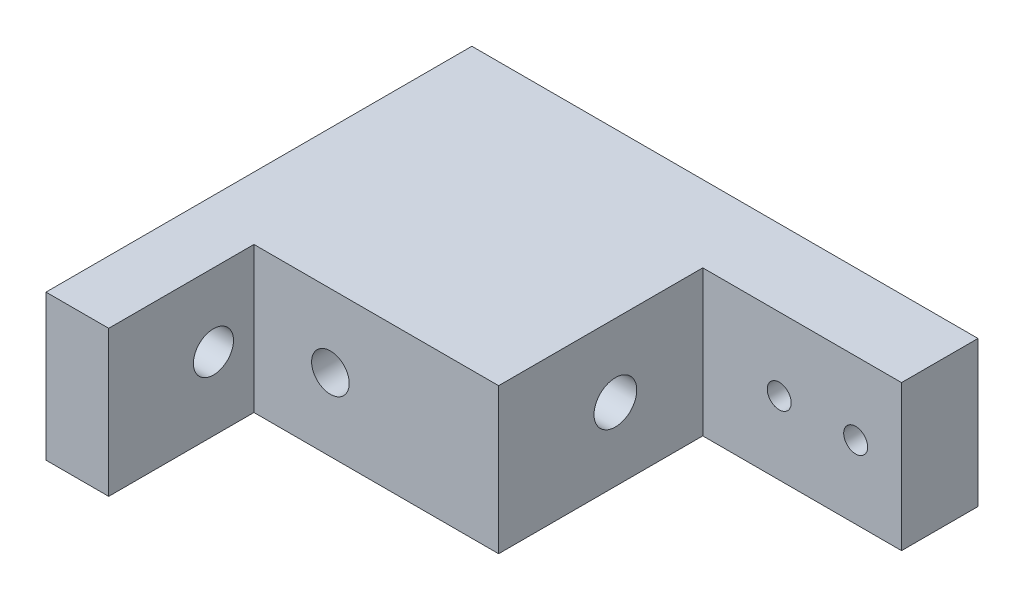
SolidWorks part; units mm, degrees
ref_plane "Front Plane" through (0, 0, 0) normal (0, 0, 1) x (1, 0, 0)
ref_plane "Top Plane" through (0, 0, 0) normal (0, 1, 0) x (1, 0, 0)
ref_plane "Right Plane" through (0, 0, 0) normal (1, 0, 0) x (0, 0, -1)
ref_plane "Plane1" through (0, -4.76, 0) normal (0, -1, 0) x (1, 0, 0)
sketch "Sketch1" plane through (0, -4.76, 0) normal (0, -1, 0) x (1, 0, 0)
  line L0 (-23.6, 0) -> (9.5, 0)
  line L1 (9.5, 0) -> (9.5, 27.85)
  line L2 (9.5, 27.85) -> (-23.6, 27.85)
  line L3 (-23.6, 27.85) -> (-23.6, 0)
extrude "Boss-Extrude1" add sketch "Sketch1" against normal blind 9.52
sketch "Sketch2" plane through (0, 4.76, 0) normal (0, 1, 0) x (-1, 0, 0)
  line L0 (-9.5, 5) -> (3.5, 5)
  line L1 (3.5, 5) -> (3.5, 27.85)
  line L2 (3.5, 27.85) -> (-9.5, 27.85)
  line L3 (-9.5, 27.85) -> (-9.5, 5)
extrude "Cut-Extrude1" cut sketch "Sketch2" against normal through all
sketch "Sketch3" plane through (0, 4.76, 0) normal (0, 1, 0) x (-1, 0, 0)
  line L0 (3.5, 18.35) -> (19.5, 18.35)
  line L1 (19.5, 18.35) -> (19.5, 27.85)
  line L2 (19.5, 27.85) -> (3.5, 27.85)
  line L3 (3.5, 27.85) -> (3.5, 18.35)
extrude "Cut-Extrude2" cut sketch "Sketch3" against normal through all
sketch "Sketch4" plane through (0, 0, 0) normal (0, 1, 0) x (1, 0, 0)
  line L0 (7.2835, 0) -> (6.5, 0)
  line L1 (6.5, 0) -> (6.5, -5)
  line L2 (6.5, -5) -> (7.2835, -5)
  line L3 (7.2835, -5) -> (7.2835, -2)
  line L4 (7.2835, -2) -> (7.2835, 0)
  line L5 (6.5, 0) -> (6.5, -5) construction
revolve "Cut-Revolve1" cut sketch "Sketch4" angle 360 about L5
sketch "Sketch5" plane through (0, 0, 0) normal (0, 1, 0) x (1, 0, 0)
  line L0 (2.2835, 0) -> (1.5, 0)
  line L1 (1.5, 0) -> (1.5, -5)
  line L2 (1.5, -5) -> (2.2835, -5)
  line L3 (2.2835, -5) -> (2.2835, -2)
  line L4 (2.2835, -2) -> (2.2835, 0)
  line L5 (1.5, 0) -> (1.5, -5) construction
revolve "Cut-Revolve2" cut sketch "Sketch5" angle 360 about L5
ref_plane "Plane2" through (0, 0, 0) normal (0, -1, 0) x (1, 0, 0)
sketch "Sketch6" plane through (0, 0, 0) normal (0, -1, 0) x (1, 0, 0)
  line L0 (-13.2705, 18.35) -> (-14.5, 18.35)
  line L1 (-14.5, 18.35) -> (-14.5, 8.35)
  line L2 (-14.5, 8.35) -> (-13.2705, 8.35)
  line L3 (-13.2705, 8.35) -> (-13.2705, 16.35)
  line L4 (-13.2705, 16.35) -> (-13.2705, 18.35)
  line L5 (-14.5, 18.35) -> (-14.5, 8.35) construction
revolve "Cut-Revolve3" cut sketch "Sketch6" angle 360 about L5
ref_plane "Plane3" through (0, 0, 21) normal (0, 0, 1) x (1, 0, 0)
sketch "Sketch7" plane through (0, 0, 21) normal (0, 0, 1) x (1, 0, 0)
  line L0 (-23.6, 1.3105) -> (-23.6, 0)
  line L1 (-23.6, 0) -> (-19.5, 0)
  line L2 (-19.5, 0) -> (-19.5, 1.3105)
  line L3 (-19.5, 1.3105) -> (-21.6, 1.3105)
  line L4 (-21.6, 1.3105) -> (-23.6, 1.3105)
  line L5 (-23.6, 0) -> (-19.5, 0) construction
revolve "Cut-Revolve4" cut sketch "Sketch7" angle 360 about L5
hole_wizard "#97 (0.0059) Diameter Hole1" positions "Sketch9" profile "Sketch8" hole size "#97" standard "ANSI Inch" end condition through all
sketch "Sketch9" plane through (-23.6, 0, 0) normal (-1, 0, 0) x (0, 0, 1)
  point P0 (10.7137, 0)
sketch "Sketch8" plane through (-23.6, 0, 10.7137) normal (0, 1, 0) x (0, 0, 1)
  line L0 (0, 0) -> (0, 33.1)
  line L1 (0, 33.1) -> (1.397, 33.1)
  line L2 (1.397, 33.1) -> (1.397, 0)
  line L5 (1.397, 0) -> (0, 0)
  line L11 (0, -6.35) -> (0, 107.95) construction
  dimension "Thru Hole Dia." = 2.794
  dimension "Thru Hole Depth" = 33.1
